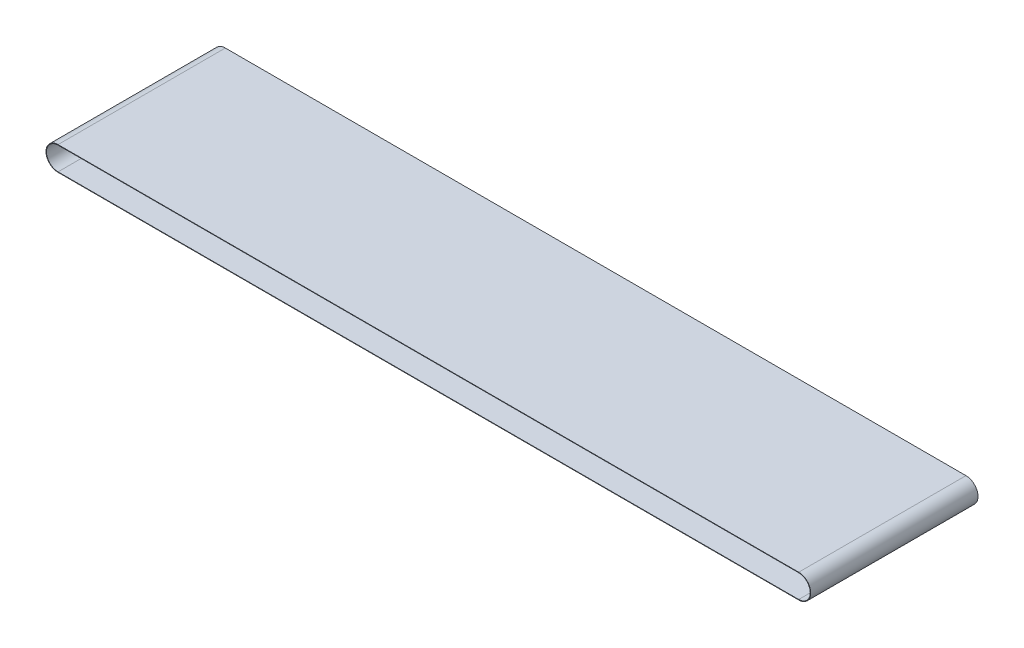
SolidWorks part; units mm, degrees
material "PUR"
ref_plane "Ön Düzlem" through (0, 0, 0) normal (0, 0, 1) x (1, 0, 0)
ref_plane "Üst Düzlem" through (0, 0, 0) normal (0, 1, 0) x (1, 0, 0)
ref_plane "Sağ Düzlem" through (0, 0, 0) normal (1, 0, 0) x (0, 0, -1)
sketch "Çizim1" plane through (0, 0, 0) normal (0, 0, 1) x (1, 0, 0)
  line L0 (0, 0) -> (4800, 0) construction
  line L1 (0, 75) -> (4800, 75)
  line L2 (0, -75) -> (4800, -75)
  arc A0 (0, 75) -> (0, -75) centre (0, 0) ccw
  arc A1 (4800, -75) -> (4800, 75) centre (4800, 0) ccw
  point P3 (2400, 0)
  dimension "D2" = 150
  dimension "D1" = 4800
extrude "Ekstrüzyon-İnce1" add sketch "Çizim1" along normal blind 1084 thin thin type one direction wall 3
